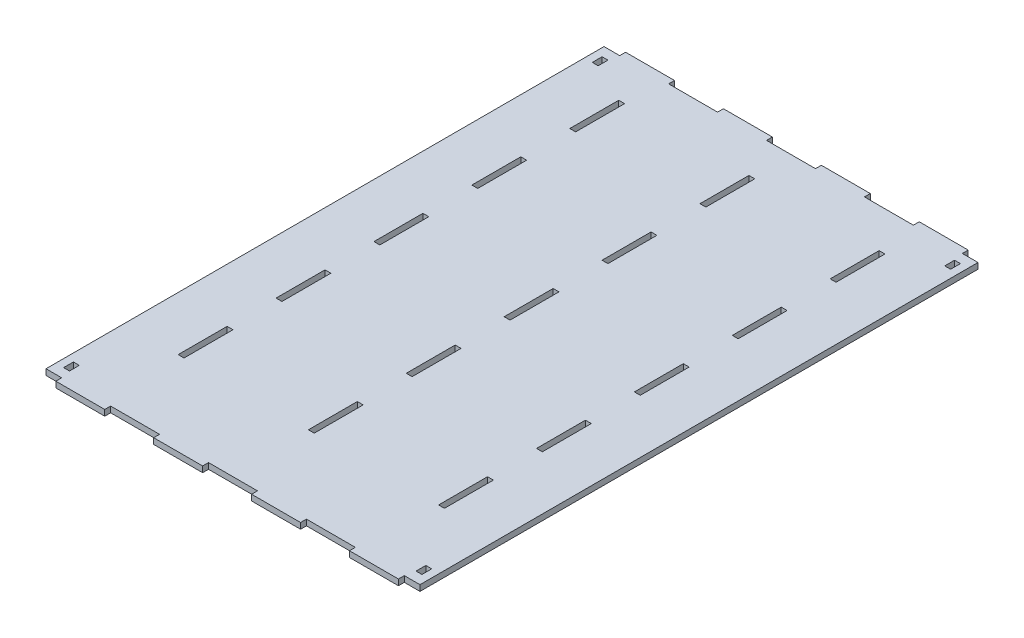
SolidWorks part; units mm, degrees
material "Buk"
ref_plane "Přední rovina" through (0, 0, 0) normal (0, 0, 1) x (1, 0, 0)
ref_plane "Horní rovina" through (0, 0, 0) normal (0, 1, 0) x (1, 0, 0)
ref_plane "Pravá rovina" through (0, 0, 0) normal (1, 0, 0) x (0, 0, -1)
sketch "Skica1" plane through (0, 0, 0) normal (0, 1, 0) x (1, 0, 0)
  line L0 (-95.5, -142.5) -> (95.5, 142.5) construction
  line L1 (-95.5, 142.5) -> (95.5, 142.5)
  line L2 (-95.5, 142.5) -> (-95.5, -142.5)
  line L3 (-95.5, -142.5) -> (95.5, -142.5)
  line L4 (95.5, 142.5) -> (95.5, -142.5)
  dimension "D1" = 191
  dimension "D2" = 285
extrude "Přidat vysunutím1" add sketch "Skica1" along normal blind 3
sketch "Skica7" plane through (0, 0, 0) normal (0, 1, 0) x (1, 0, 0)
  line L0 (-95.5, -142.5) -> (95.5, -142.5) construction
  line L1 (-87.5, -142.5) -> (-62.5, -142.5)
  line L2 (-87.5, -142.5) -> (-87.5, -145.5)
  line L3 (-87.5, -145.5) -> (-62.5, -145.5)
  line L4 (-62.5, -142.5) -> (-62.5, -145.5)
  line L5 (0, 0) -> (0, -50.8715) construction
  line L6 (-37.5, -142.5) -> (-12.5, -142.5)
  line L7 (-37.5, -142.5) -> (-37.5, -145.5)
  line L8 (-37.5, -145.5) -> (-12.5, -145.5)
  line L9 (-12.5, -142.5) -> (-12.5, -145.5)
  line L10 (12.5, -142.5) -> (37.5, -142.5)
  line L11 (12.5, -142.5) -> (12.5, -145.5)
  line L12 (12.5, -145.5) -> (37.5, -145.5)
  line L13 (37.5, -142.5) -> (37.5, -145.5)
  line L14 (62.5, -142.5) -> (87.5, -142.5)
  line L15 (0, 0) -> (42.3966, 0) construction
  line L16 (62.5, -142.5) -> (62.5, -145.5)
  line L17 (62.5, -145.5) -> (87.5, -145.5)
  line L18 (87.5, -142.5) -> (87.5, -145.5)
  line L19 (-62.5, -145.5) -> (-37.5, -145.5) construction
  line L20 (-62.5, 145.5) -> (-37.5, 145.5) construction
  line L21 (87.5, 142.5) -> (87.5, 145.5)
  line L22 (62.5, 145.5) -> (87.5, 145.5)
  line L23 (62.5, 142.5) -> (62.5, 145.5)
  line L24 (62.5, 142.5) -> (87.5, 142.5)
  line L25 (37.5, 142.5) -> (37.5, 145.5)
  line L26 (12.5, 145.5) -> (37.5, 145.5)
  line L27 (12.5, 142.5) -> (12.5, 145.5)
  line L28 (12.5, 142.5) -> (37.5, 142.5)
  line L29 (-12.5, 142.5) -> (-12.5, 145.5)
  line L30 (-37.5, 145.5) -> (-12.5, 145.5)
  line L31 (-37.5, 142.5) -> (-37.5, 145.5)
  line L32 (-37.5, 142.5) -> (-12.5, 142.5)
  line L33 (-62.5, 142.5) -> (-62.5, 145.5)
  line L34 (-87.5, 145.5) -> (-62.5, 145.5)
  line L35 (-87.5, 142.5) -> (-87.5, 145.5)
  line L36 (-87.5, 142.5) -> (-62.5, 142.5)
  dimension "D1" = 25
  dimension "D2" = 3
  dimension "D3" = 4
extrude "Přidat vysunutím2" add sketch "Skica7" along normal up to surface (3 mm away) up to face at (0, 3, 0)
sketch "Skica6" plane through (0, 0, 0) normal (0, 1, 0) x (1, 0, 0)
  line L1 (-91.5, -132.5) -> (-88.5, -132.5)
  line L2 (-91.5, -132.5) -> (-91.5, -137.5)
  line L3 (-91.5, -137.5) -> (-88.5, -137.5)
  line L4 (-88.5, -132.5) -> (-88.5, -137.5)
  line L5 (-95.5, 142.5) -> (-95.5, -142.5) construction
  line L7 (0, 189.7913) -> (0, -189.7913) construction
  line L8 (88.5, -132.5) -> (88.5, -137.5)
  line L9 (91.5, -137.5) -> (88.5, -137.5)
  line L10 (91.5, -132.5) -> (91.5, -137.5)
  line L11 (91.5, -132.5) -> (88.5, -132.5)
  line L12 (0, 0) -> (282.485, 0) construction
  line L13 (91.5, 132.5) -> (88.5, 132.5)
  line L14 (91.5, 132.5) -> (91.5, 137.5)
  line L15 (91.5, 137.5) -> (88.5, 137.5)
  line L16 (88.5, 132.5) -> (88.5, 137.5)
  line L17 (-88.5, 132.5) -> (-88.5, 137.5)
  line L18 (-91.5, 137.5) -> (-88.5, 137.5)
  line L19 (-91.5, 132.5) -> (-91.5, 137.5)
  line L20 (-91.5, 132.5) -> (-88.5, 132.5)
  line L21 (-95.5, -142.5) -> (-87.5, -142.5) construction
  line L22 (-87.5, -142.5) -> (-87.5, -145.5) construction
  dimension "D1" = 5
  dimension "D2" = 5
  dimension "D3" = 4
extrude "Odebrat vysunutím6" cut sketch "Skica6" along normal through all
sketch "Skica4" plane through (0, 0, 0) normal (0, 1, 0) x (1, 0, 0)
  line L0 (-68, 97.5) -> (-65, 97.5)
  line L1 (-1.5, 122.5) -> (1.5, 122.5)
  line L2 (-1.5, 122.5) -> (-1.5, 97.5)
  line L3 (-1.5, 97.5) -> (1.5, 97.5)
  line L4 (1.5, 122.5) -> (1.5, 97.5)
  line L5 (-68, 122.5) -> (-65, 122.5)
  line L6 (-68, 122.5) -> (-68, 97.5)
  line L8 (-65, 122.5) -> (-65, 97.5)
  line L9 (65, 122.5) -> (68, 122.5)
  line L10 (65, 122.5) -> (65, 97.5)
  line L11 (65, 97.5) -> (68, 97.5)
  line L12 (68, 122.5) -> (68, 97.5)
  line L13 (-65, 122.5) -> (65, 122.5) construction
  line L14 (65, 72.5) -> (68, 72.5)
  line L15 (0, 122.5) -> (0, 133.6533) construction
  line L16 (-95.5, 142.5) -> (-95.5, -142.5) construction
  line L17 (95.5, -142.5) -> (95.5, 142.5) construction
  line L18 (65, 72.5) -> (65, 47.5)
  line L19 (65, 47.5) -> (68, 47.5)
  line L20 (68, 72.5) -> (68, 47.5)
  line L21 (-1.5, 72.5) -> (1.5, 72.5)
  line L22 (-1.5, 72.5) -> (-1.5, 47.5)
  line L23 (-1.5, 47.5) -> (1.5, 47.5)
  line L24 (1.5, 72.5) -> (1.5, 47.5)
  line L25 (-68, 47.5) -> (-65, 47.5)
  line L26 (-68, 72.5) -> (-65, 72.5)
  line L27 (-68, 72.5) -> (-68, 47.5)
  line L28 (-65, 72.5) -> (-65, 47.5)
  line L29 (65, 22.5) -> (68, 22.5)
  line L30 (65, 22.5) -> (65, -2.5)
  line L31 (65, -2.5) -> (68, -2.5)
  line L32 (68, 22.5) -> (68, -2.5)
  line L33 (-1.5, 22.5) -> (1.5, 22.5)
  line L34 (-1.5, 22.5) -> (-1.5, -2.5)
  line L35 (-1.5, -2.5) -> (1.5, -2.5)
  line L36 (1.5, 22.5) -> (1.5, -2.5)
  line L37 (-68, -2.5) -> (-65, -2.5)
  line L38 (-68, 22.5) -> (-65, 22.5)
  line L39 (-68, 22.5) -> (-68, -2.5)
  line L40 (-65, 22.5) -> (-65, -2.5)
  line L41 (65, -27.5) -> (68, -27.5)
  line L42 (65, -27.5) -> (65, -52.5)
  line L43 (65, -52.5) -> (68, -52.5)
  line L45 (68, -27.5) -> (68, -52.5)
  line L46 (-1.5, -27.5) -> (1.5, -27.5)
  line L47 (-1.5, -27.5) -> (-1.5, -52.5)
  line L48 (-1.5, -52.5) -> (1.5, -52.5)
  line L49 (1.5, -27.5) -> (1.5, -52.5)
  line L50 (-68, -52.5) -> (-65, -52.5)
  line L51 (-68, -27.5) -> (-65, -27.5)
  line L52 (-68, -27.5) -> (-68, -52.5)
  line L53 (-65, -27.5) -> (-65, -52.5)
  line L54 (65, -77.5) -> (68, -77.5)
  line L55 (65, -77.5) -> (65, -102.5)
  line L56 (65, -102.5) -> (68, -102.5)
  line L57 (-62.5, 145.5) -> (-87.5, 145.5) construction
  line L58 (-62.5, 142.5) -> (-62.5, 145.5) construction
  line L59 (68, -77.5) -> (68, -102.5)
  line L60 (-1.5, -77.5) -> (1.5, -77.5)
  line L61 (-1.5, -77.5) -> (-1.5, -102.5)
  line L62 (-1.5, -102.5) -> (1.5, -102.5)
  line L63 (1.5, -77.5) -> (1.5, -102.5)
  line L64 (-68, -102.5) -> (-65, -102.5)
  line L65 (-68, -77.5) -> (-65, -77.5)
  line L66 (-68, -77.5) -> (-68, -102.5)
  line L67 (-65, -77.5) -> (-65, -102.5)
  line L69 (-68, 97.5) -> (-68, 72.5) construction
  line L70 (-37.5, 142.5) -> (-62.5, 142.5) construction
  dimension "D1" = 5
  dimension "D2" = 245
  dimension "D4" = 130
extrude "Odebrat vysunutím3" cut sketch "Skica4" along normal through all
sketch "Skica5" plane through (0, 0, 0) normal (0, 1, 0) x (1, 0, 0)
  line L1 (-95.5, 142.5) -> (-95.5, -142.5) construction
  line L2 (-88.5, 137.5) -> (-85.5, 137.5)
  line L3 (-88.5, 137.5) -> (-88.5, 112.5)
  line L4 (-88.5, 112.5) -> (-85.5, 112.5)
  line L5 (-85.5, 137.5) -> (-85.5, 112.5)
  line L6 (-62.5, 142.5) -> (-62.5, 145.5) construction
  line L7 (-62.5, 145.5) -> (-87.5, 145.5) construction
  line L8 (-1.5, 137.5) -> (1.5, 137.5)
  line L9 (-1.5, 137.5) -> (-1.5, 112.5)
  line L10 (-1.5, 112.5) -> (1.5, 112.5)
  line L11 (1.5, 137.5) -> (1.5, 112.5)
  line L12 (-88.5, 87.5) -> (-85.5, 87.5)
  line L13 (-88.5, 87.5) -> (-88.5, 62.5)
  line L14 (-88.5, 62.5) -> (-85.5, 62.5)
  line L15 (-85.5, 87.5) -> (-85.5, 62.5)
  line L16 (-1.5, 87.5) -> (1.5, 87.5)
  line L17 (-1.5, 87.5) -> (-1.5, 62.5)
  line L18 (-1.5, 62.5) -> (1.5, 62.5)
  line L19 (1.5, 87.5) -> (1.5, 62.5)
  line L20 (85.5, 87.5) -> (85.5, 62.5)
  line L21 (88.5, 62.5) -> (85.5, 62.5)
  line L22 (88.5, 87.5) -> (88.5, 62.5)
  line L23 (88.5, 87.5) -> (85.5, 87.5)
  line L24 (-88.5, 37.5) -> (-85.5, 37.5)
  line L25 (-88.5, 37.5) -> (-88.5, 12.5)
  line L26 (-88.5, 12.5) -> (-85.5, 12.5)
  line L27 (-85.5, 112.5) -> (-85.5, 87.5) construction
  line L28 (-85.5, 37.5) -> (-85.5, 12.5)
  line L29 (-1.5, 37.5) -> (1.5, 37.5)
  line L30 (0, 0) -> (-52.6794, 0) construction
  line L31 (-1.5, 37.5) -> (-1.5, 12.5)
  line L32 (-1.5, 12.5) -> (1.5, 12.5)
  line L33 (1.5, 37.5) -> (1.5, 12.5)
  line L34 (85.5, 37.5) -> (85.5, 12.5)
  line L35 (88.5, 12.5) -> (85.5, 12.5)
  line L36 (88.5, 37.5) -> (88.5, 12.5)
  line L37 (88.5, 37.5) -> (85.5, 37.5)
  line L38 (-88.5, -12.5) -> (-85.5, -12.5)
  line L39 (-88.5, -12.5) -> (-88.5, -37.5)
  line L40 (-88.5, -37.5) -> (-85.5, -37.5)
  line L41 (-85.5, -12.5) -> (-85.5, -37.5)
  line L42 (-1.5, -12.5) -> (1.5, -12.5)
  line L43 (-1.5, -12.5) -> (-1.5, -37.5)
  line L44 (-1.5, -37.5) -> (1.5, -37.5)
  line L45 (1.5, -12.5) -> (1.5, -37.5)
  line L46 (85.5, -12.5) -> (85.5, -37.5)
  line L47 (88.5, -37.5) -> (85.5, -37.5)
  line L48 (88.5, -12.5) -> (88.5, -37.5)
  line L49 (88.5, -12.5) -> (85.5, -12.5)
  line L50 (-88.5, -62.5) -> (-85.5, -62.5)
  line L51 (-88.5, -62.5) -> (-88.5, -87.5)
  line L52 (85.5, 137.5) -> (85.5, 112.5)
  line L53 (88.5, 112.5) -> (85.5, 112.5)
  line L54 (88.5, 137.5) -> (88.5, 112.5)
  line L55 (88.5, 137.5) -> (85.5, 137.5)
  line L56 (-88.5, -87.5) -> (-85.5, -87.5)
  line L57 (-85.5, -62.5) -> (-85.5, -87.5)
  line L58 (-1.5, -62.5) -> (1.5, -62.5)
  line L59 (-1.5, -62.5) -> (-1.5, -87.5)
  line L60 (-1.5, -87.5) -> (1.5, -87.5)
  line L61 (1.5, -62.5) -> (1.5, -87.5)
  line L62 (85.5, -62.5) -> (85.5, -87.5)
  line L63 (88.5, -87.5) -> (85.5, -87.5)
  line L64 (88.5, -62.5) -> (88.5, -87.5)
  line L65 (88.5, -62.5) -> (85.5, -62.5)
  line L66 (-88.5, -112.5) -> (-85.5, -112.5)
  line L67 (-88.5, -112.5) -> (-88.5, -137.5)
  line L68 (-88.5, -137.5) -> (-85.5, -137.5)
  line L69 (-85.5, -112.5) -> (-85.5, -137.5)
  line L70 (-1.5, -112.5) -> (1.5, -112.5)
  line L71 (-1.5, -112.5) -> (-1.5, -137.5)
  line L72 (-1.5, -137.5) -> (1.5, -137.5)
  line L73 (1.5, -112.5) -> (1.5, -137.5)
  line L74 (85.5, -112.5) -> (85.5, -137.5)
  line L75 (88.5, -137.5) -> (85.5, -137.5)
  line L76 (88.5, -112.5) -> (88.5, -137.5)
  line L77 (88.5, -112.5) -> (85.5, -112.5)
  line L78 (-88.5, 112.5) -> (-88.5, 87.5) construction
  line L121 (0, 0) -> (0, 228.487) construction
  dimension "D1" = 7
  dimension "D2" = 6
extrude "Odebrat vysunutím5" [suppressed] cut sketch "Skica5" along normal through all
